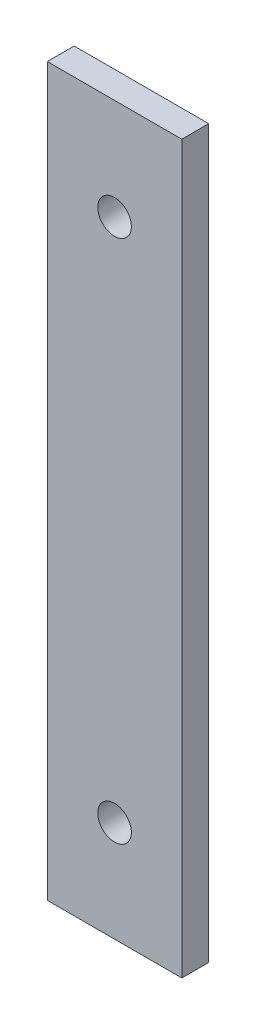
SolidWorks part; units mm, degrees
material "自訂玻璃纖維"
ref_plane "前基準面" through (0, 0, 0) normal (0, 0, 1) x (1, 0, 0)
ref_plane "上基準面" through (0, 0, 0) normal (0, 1, 0) x (1, 0, 0)
ref_plane "右基準面" through (0, 0, 0) normal (1, 0, 0) x (0, 0, -1)
sketch "草圖1" plane through (0, 0, 0) normal (0, 0, 1) x (1, 0, 0)
  line L1 (-6.729, 13.866) -> (3.271, 13.866)
  line L2 (-6.729, 13.866) -> (-6.729, -40.134)
  line L3 (-6.729, -40.134) -> (3.271, -40.134)
  line L4 (3.271, 13.866) -> (3.271, -40.134)
  circle A0 centre (-1.729, 6.366) radius 1.25
  circle A1 centre (-1.729, -32.634) radius 1.25
  dimension "D3" = 2.5
  dimension "D4" = 7.5
  dimension "D5" = 2.5
  dimension "D6" = 7.5
  dimension "D1" = 10
  dimension "D2" = 54
extrude "填料-伸長1" add sketch "草圖1" along normal blind 2
